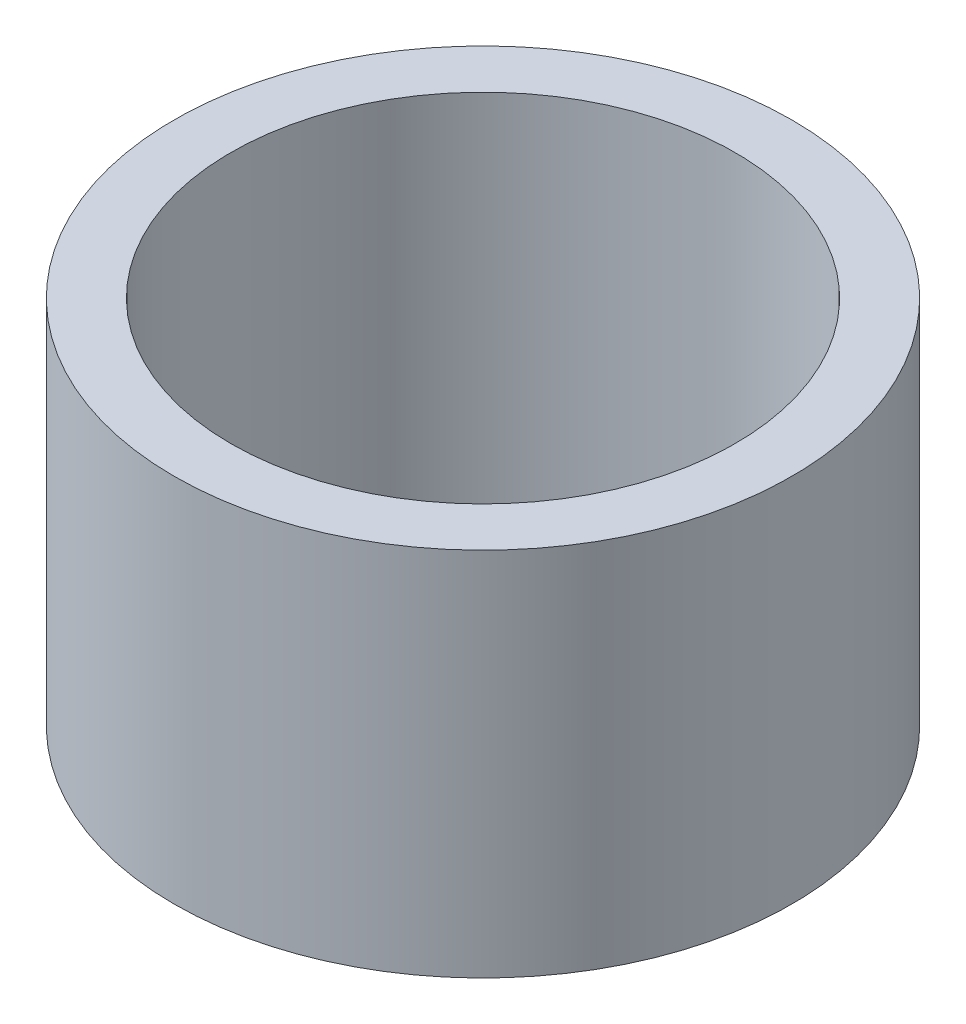
SolidWorks part; units mm, degrees
material "Q235A"
ref_plane "前视" through (0, 0, 0) normal (0, 0, 1) x (1, 0, 0)
ref_plane "上视" through (0, 0, 0) normal (0, 1, 0) x (1, 0, 0)
ref_plane "右视" through (0, 0, 0) normal (1, 0, 0) x (0, 0, -1)
sketch "草图1" plane through (0, 0, 0) normal (0, 1, 0) x (1, 0, 0)
  circle A0 centre (0, 0) radius 30
  circle A1 centre (0, 0) radius 24.5
  dimension "D1" = 49
  dimension "D2" = 60
extrude "凸台-拉伸1" add sketch "草图1" along normal mid plane 36
